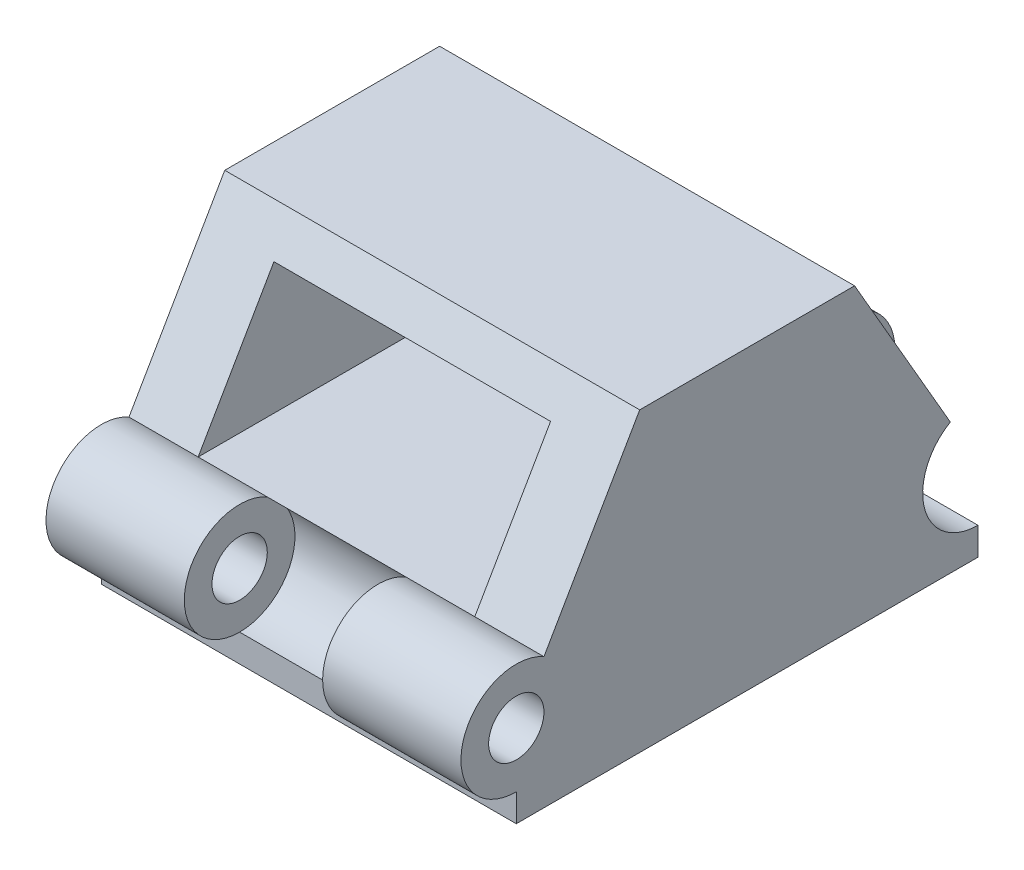
SolidWorks part; units mm, degrees
ref_plane "정면" through (0, 0, 0) normal (0, 0, 1) x (1, 0, 0)
ref_plane "윗면" through (0, 0, 0) normal (0, 1, 0) x (1, 0, 0)
ref_plane "우측면" through (0, 0, 0) normal (1, 0, 0) x (0, 0, -1)
sketch "스케치1" plane through (0, 0, 0) normal (1, 0, 0) x (0, 0, -1)
  line L0 (0, 0) -> (9.5, 16.4545)
  line L1 (9.5, 16.4545) -> (28.5, 16.4545)
  line L2 (28.5, 16.4545) -> (38, 0)
  line L3 (38, 0) -> (0, 0)
  dimension "D1" = 19
  dimension "D2" = 19
  dimension "D3" = 19
  dimension "D4" = 60
extrude "보스-돌출1" add sketch "스케치1" along normal blind 30
sketch "스케치2" plane through (0, 0, 0) normal (0, 0, 1) x (1, 0, 0)
  line L1 (5, 13.4545) -> (25, 13.4545)
  line L2 (5, 13.4545) -> (5, 3)
  line L3 (5, 3) -> (25, 3)
  line L4 (25, 13.4545) -> (25, 3)
  line L5 (30, 16.4545) -> (30, 0) construction
  line L6 (0, 16.4545) -> (0, 0) construction
  line L7 (30, 16.4545) -> (0, 16.4545) construction
  line L8 (30, 0) -> (0, 0) construction
  dimension "D1" = 5
  dimension "D2" = 5
  dimension "D3" = 3
  dimension "D4" = 3
extrude "컷-돌출1" cut sketch "스케치2" against normal through all
sketch "스케치3" plane through (30, 0, 0) normal (1, 0, 0) x (0, 0, -1)
  line L0 (38, 0) -> (28.5, 16.4545) construction
  line L1 (38, 0) -> (37.6906, 0.5359)
  line L2 (38, 0) -> (35.6906, 0)
  circle A0 centre (35.6906, 4) radius 4
  line M1 (0, 0) -> (38, 0)
  line M2 (38, 0) -> (28.5, 16.4545)
  dimension "D1" = 8
extrude "컷-돌출4" cut sketch "스케치3" against normal through all contours A0 M2 | A0 M1 M2
sketch "스케치4" plane through (30, 0, 0) normal (1, 0, 0) x (0, 0, -1)
  circle A0 centre (35.6906, 4) radius 4
  circle A1 centre (35.6906, 4) radius 2
  dimension "D1" = 8
  dimension "D2" = 4
extrude "보스-돌출2" add sketch "스케치4" against normal blind 30
sketch "스케치5" plane through (30, 0, 0) normal (1, 0, 0) x (0, 0, -1)
  line L2 (0.3094, 0.5359) -> (0, 0)
  line L3 (0, 0) -> (2.3094, 0)
  line L4 (9.5, 16.4545) -> (0, 0) construction
  circle A0 centre (2.3094, 4) radius 4
  line M1 (0, 0) -> (35.6906, 0)
  line M5 (9.5, 16.4545) -> (0, 0)
  dimension "D1" = 8
extrude "컷-돌출5" cut sketch "스케치5" against normal through all contours A0 M5 | A0 M5 M1
sketch "스케치6" plane through (30, 0, 0) normal (1, 0, 0) x (0, 0, -1)
  circle A0 centre (2.3094, 4) radius 4
  circle A1 centre (2.3094, 4) radius 2
  dimension "D1" = 4
extrude "보스-돌출3" add sketch "스케치6" against normal blind 30
sketch "스케치7" plane through (30, 0, 0) normal (1, 0, 0) x (0, 0, -1)
  circle A0 centre (2.3094, 4) radius 4
  circle A1 centre (2.3094, 4) radius 2
  arc A2 (4.3094, 7.4641) -> (2.3094, 0) centre (2.3094, 4) ccw construction
  circle A3 centre (2.3094, 4) radius 2 construction
extrude "컷-돌출8" cut sketch "스케치7" against normal blind 10 from offset 10 offset against normal yes
sketch "스케치8" plane through (30, 0, 0) normal (1, 0, 0) x (0, 0, -1)
  circle A0 centre (35.6906, 4) radius 4
  circle A1 centre (35.6906, 4) radius 2
  circle A2 centre (35.6906, 4) radius 2 construction
  arc A3 (35.6906, 0) -> (33.6906, 7.4641) centre (35.6906, 4) ccw construction
extrude "컷-돌출9" cut sketch "스케치8" against normal blind 10
sketch "스케치9" plane through (30, 0, 0) normal (1, 0, 0) x (0, 0, -1)
  circle A0 centre (35.6906, 4) radius 4
  circle A1 centre (35.6906, 4) radius 2
  circle A2 centre (35.6906, 4) radius 2 construction
  arc A3 (35.6906, 0) -> (31.8176, 3) centre (35.6906, 4) ccw construction
extrude "컷-돌출10" cut sketch "스케치9" against normal blind 10 from offset 20 offset against normal yes
sketch "스케치11" plane through (30, 0, 0) normal (1, 0, 0) x (0, 0, -1)
  line L0 (4.3094, 7.4641) -> (33.6906, 7.4641)
  line L1 (35.6906, 0) -> (2.3094, 0)
  arc A0 (33.6906, 7.4641) -> (35.6906, 0) centre (35.6906, 4) ccw construction
  arc A1 (4.3094, 7.4641) -> (2.3094, 0) centre (2.3094, 4) cw
  arc A2 (33.6906, 7.4641) -> (35.6906, 0) centre (35.6906, 4) ccw
  dimension "D1" = 4
extrude "보스-돌출4" add sketch "스케치11" against normal blind 30
sketch "스케치12" plane through (0, 0, 0) normal (-1, 0, 0) x (0, 0, 1)
  line L1 (-35.6906, 0) -> (-2.3094, 0)
  line L2 (-35.6906, 0) -> (-35.6906, -2)
  line L3 (-35.6906, -2) -> (-2.3094, -2)
  line L4 (-2.3094, 0) -> (-2.3094, -2)
  arc A1 (-2.3094, 0) -> (-4.3094, 7.4641) centre (-2.3094, 4) ccw construction
  point P0 (-2.3094, 0)
  dimension "D1" = 2
extrude "보스-돌출5" add sketch "스케치12" against normal blind 30
sketch "스케치14" plane through (30, 0, 0) normal (1, 0, 0) x (0, 0, -1)
  line L0 (28.5, 16.4545) -> (26.7679, 19.4545)
  line L1 (26.7679, 19.4545) -> (11.2321, 19.4545)
  line L2 (11.2321, 19.4545) -> (9.5, 16.4545)
  line L3 (9.5, 16.4545) -> (4.3094, 7.4641) construction
  line L4 (33.6906, 7.4641) -> (28.5, 16.4545) construction
  line L5 (28.5, 16.4545) -> (9.5, 16.4545) construction
  line L12 (9.5, 16.4545) -> (4.3094, 7.4641)
  line L13 (2.3094, 0) -> (2.3094, -2)
  line L14 (2.3094, -2) -> (35.6906, -2)
  line L15 (35.6906, -2) -> (35.6906, 0)
  line L16 (33.6906, 7.4641) -> (28.5, 16.4545)
  line L17 (28.5, 16.4545) -> (9.5, 16.4545)
  line L23 (28.5, 16.4545) -> (9.5, 16.4545)
  arc A2 (4.3094, 7.4641) -> (2.3094, 0) centre (2.3094, 4) ccw
  arc A3 (33.6906, 7.4641) -> (35.6906, 0) centre (35.6906, 4) ccw
  dimension "D1" = 3
  dimension "D2" = 0
extrude "보스-돌출6" add sketch "스케치14" against normal blind 30
sketch "스케치13" plane through (0, 0, -35.6906) normal (0, 0, -1) x (-1, 0, 0)
  line L0 (-5, 13.4545) -> (-5, 7.4641) construction
  line L1 (-25, 13.4545) -> (-5, 13.4545)
  line L2 (-25, 13.4545) -> (-25, 16.9545)
  line L3 (-25, 16.9545) -> (-5, 16.9545)
  line L4 (-5, 13.4545) -> (-5, 16.9545)
  point P5 (-5, 13.4545)
  dimension "D1" = 3.5
extrude "컷-돌출11" cut sketch "스케치13" against normal blind 30
sketch "스케치15" plane through (0, 0, -2.3094) normal (0, 0, 1) x (1, 0, 0)
  point P2 (7.5785, 7.9888)
sketch "스케치18" plane through (0, 0, -2.3094) normal (0, 0, 1) x (1, 0, 0)
  point P0 (7.5785, 7.9888)
